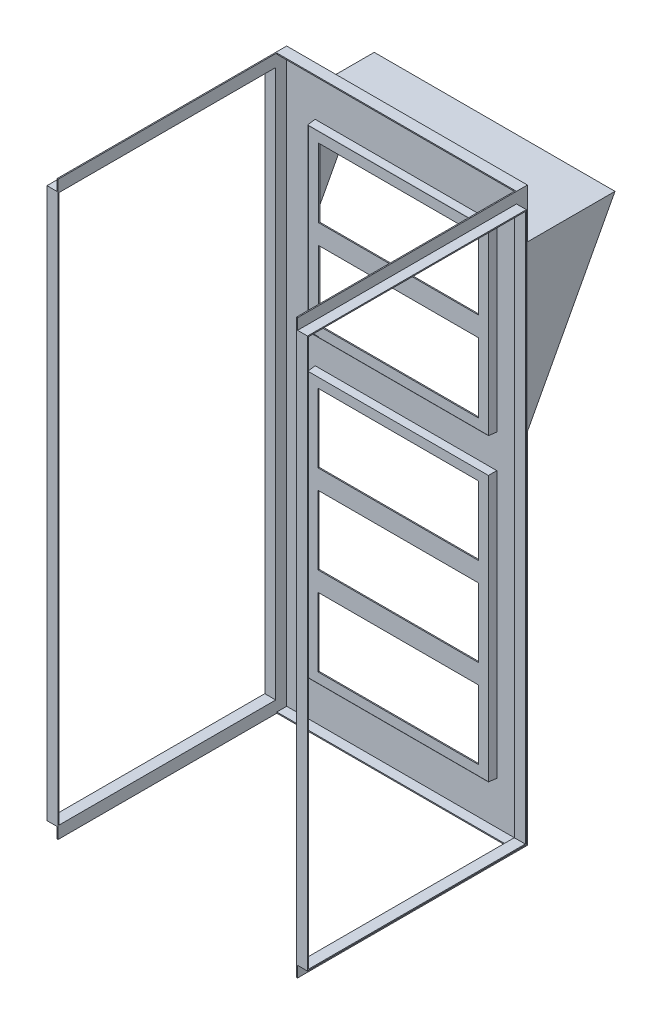
SolidWorks part; units mm, degrees
ref_plane "정면" through (0, 0, 0) normal (0, 0, 1) x (1, 0, 0)
ref_plane "윗면" through (0, 0, 0) normal (0, 1, 0) x (1, 0, 0)
ref_plane "우측면" through (0, 0, 0) normal (1, 0, 0) x (0, 0, -1)
sketch "스케치1" plane through (0, 0, 0) normal (0, 0, 1) x (1, 0, 0)
  line L1 (0, 0) -> (44, 0)
  line L2 (0, 0) -> (0, 104.5)
  line L3 (0, 104.5) -> (44, 104.5)
  line L4 (44, 0) -> (44, 104.5)
  dimension "D1" = 104.5
  dimension "D2" = 44
extrude "보스-돌출1" add sketch "스케치1" along normal blind 2
shell "쉘1" thickness 0.2
sketch "스케치2" plane through (0, 0, 0.2) normal (0, 0, 1) x (1, 0, 0)
  line L0 (44, 104.5) -> (0, 104.5) construction
  line L1 (5.6, 95.5) -> (38.4, 95.5)
  line L2 (5.6, 95.5) -> (5.6, 63)
  line L3 (5.6, 63) -> (38.4, 63)
  line L4 (38.4, 95.5) -> (38.4, 63)
  line L5 (5.6, 56.5) -> (38.4, 56.5)
  line L6 (5.6, 56.5) -> (5.6, 8.2)
  line L7 (5.6, 8.2) -> (38.4, 8.2)
  line L8 (38.4, 56.5) -> (38.4, 8.2)
  line L9 (0.2, 0.2) -> (43.8, 0.2) construction
  line L12 (0, 104.5) -> (0, 0) construction
  point P14 (22, 95.5)
  point P15 (22, 56.5)
  dimension "D1" = 9
  dimension "D2" = 32.5
  dimension "D3" = 6.5
  dimension "D4" = 8
  dimension "D5" = 32.8
  dimension "D6" = 32.8
  dimension "D7" = 22
  dimension "D8" = 22
extrude "컷-돌출1" cut sketch "스케치2" against normal blind 2
sketch "스케치3" plane through (0, 0, 0.2) normal (0, 0, 1) x (1, 0, 0)
  line L0 (5.6, 8.2) -> (38.4, 8.2) construction
  line L1 (5.6, 56.5) -> (5.6, 8.2) construction
  line L2 (38.4, 56.5) -> (5.6, 56.5) construction
  line L3 (38.4, 8.2) -> (38.4, 56.5) construction
  line L4 (5.6, 63) -> (38.4, 63)
  line L5 (5.6, 95.5) -> (5.6, 63)
  line L6 (38.4, 95.5) -> (5.6, 95.5)
  line L7 (38.4, 63) -> (38.4, 95.5)
  line L8 (5.6, 63) -> (38.4, 63)
  line L9 (5.6, 95.5) -> (5.6, 63)
  line L10 (38.4, 95.5) -> (5.6, 95.5)
  line L11 (38.4, 63) -> (38.4, 95.5)
  line L12 (5.6, 8.2) -> (38.4, 8.2)
  line L13 (5.6, 56.5) -> (5.6, 8.2)
  line L14 (38.4, 56.5) -> (5.6, 56.5)
  line L15 (38.4, 8.2) -> (38.4, 56.5)
  line L16 (5.4, 62.8) -> (38.6, 62.8)
  line L17 (38.6, 62.8) -> (38.6, 95.7)
  line L18 (38.6, 95.7) -> (5.4, 95.7)
  line L19 (5.4, 95.7) -> (5.4, 62.8)
  line L20 (5.4, 8) -> (38.6, 8)
  line L21 (38.6, 8) -> (38.6, 56.7)
  line L22 (38.6, 56.7) -> (5.4, 56.7)
  line L23 (5.4, 56.7) -> (5.4, 8)
  dimension "D1" = 0
  dimension "D2" = 0.2
extrude "보스-돌출2" add sketch "스케치3" along normal blind 1.8 draft 4
ref_plane "평면1" through (38.5, 95.6, 1.6301) normal (0, 1, 0) x (1, 0, 0)
ref_plane "평면2" through (0, 0, 1.4) normal (0, 0, 1) x (1, 0, 0)
sketch "스케치6" plane through (0, 0, 1.4) normal (0, 0, 1) x (1, 0, 0)
  line L0 (5.6, 63) -> (38.4, 63) construction
  line L1 (5.6, 95.5) -> (7.45, 95.5)
  line L2 (5.6, 95.5) -> (5.6, 63)
  line L3 (5.6, 63) -> (7.45, 63)
  line L4 (7.45, 95.5) -> (7.45, 63)
  line L6 (7.45, 64.75) -> (38.5, 64.75)
  line L7 (7.45, 64.75) -> (7.45, 62.9)
  line L8 (7.45, 62.9) -> (38.5, 62.9)
  line L9 (38.5, 64.75) -> (38.5, 62.9)
  line L11 (36.65, 64.75) -> (38.5, 64.75)
  line L12 (36.65, 64.75) -> (36.65, 95.6)
  line L13 (36.65, 95.6) -> (38.5, 95.6)
  line L14 (38.5, 64.75) -> (38.5, 95.6)
  line L15 (47.4925, 95.6) -> (29.5075, 95.6) construction
  line L16 (36.65, 93.65) -> (7.45, 93.65)
  line L17 (36.65, 93.65) -> (36.65, 95.5)
  line L18 (36.65, 95.5) -> (7.45, 95.5)
  line L19 (7.45, 93.65) -> (7.45, 95.5)
  line L20 (36.65, 77.45) -> (7.45, 77.45)
  line L21 (36.65, 77.45) -> (36.65, 81.05)
  line L22 (36.65, 81.05) -> (7.45, 81.05)
  line L23 (7.45, 77.45) -> (7.45, 81.05)
  line L24 (38.5, 62.9) -> (38.5, 95.6) construction
  dimension "D1" = 1.85
  dimension "D2" = 1.85
  dimension "D3" = 1.85
  dimension "D4" = 1.85
  dimension "D5" = 3.6
  dimension "D6" = 12.6
extrude "보스-돌출3" add sketch "스케치6" along normal blind 0.2 separate body contours L4 L1 L2 L3 | L9 L6 L4 L8 | L6 L14 L13 L12 | L12 L22 L4 L20 | L12 L18 L4 L16
sketch "스케치7" plane through (0, 0, 1.4) normal (0, 0, 1) x (1, 0, 0)
  line L1 (5.5, 56.6) -> (38.5, 56.6)
  line L2 (5.5, 56.6) -> (5.5, 8.1)
  line L3 (5.5, 8.1) -> (38.5, 8.1)
  line L4 (38.5, 56.6) -> (38.5, 8.1)
  line L5 (7.35, 22.5) -> (36.65, 22.5)
  line L6 (7.35, 22.5) -> (7.35, 9.9)
  line L7 (7.35, 9.9) -> (36.65, 9.9)
  line L8 (36.65, 22.5) -> (36.65, 9.9)
  line L9 (7.35, 38.65) -> (36.65, 38.65)
  line L10 (7.35, 38.65) -> (7.35, 26.05)
  line L11 (7.35, 26.05) -> (36.65, 26.05)
  line L12 (36.65, 38.65) -> (36.65, 26.05)
  line L13 (7.35, 54.8) -> (36.65, 54.8)
  line L14 (7.35, 54.8) -> (7.35, 42.2)
  line L15 (7.35, 42.2) -> (36.65, 42.2)
  line L16 (36.65, 54.8) -> (36.65, 42.2)
  dimension "D1" = 1.8
  dimension "D2" = 3.55
  dimension "D3" = 3.55
  dimension "D4" = 12.6
  dimension "D5" = 1.85
  dimension "D6" = 1.85
  dimension "D7" = 1.85
  dimension "D8" = 1.85
extrude "보스-돌출4" add sketch "스케치7" along normal blind 0.2
sketch "스케치11" plane through (0, 0, 0) normal (-1, 0, 0) x (0, 0, 1)
  line L0 (0, 95.5) -> (-16, 95.5)
  line L1 (0, 104.5) -> (0, 0) construction
  line L2 (-16, 95.5) -> (0, 65.5)
  line L3 (2, 104.5) -> (0, 104.5) construction
  line L4 (0, 95.5) -> (0, 65.5)
  dimension "D1" = 9
  dimension "D2" = 16
  dimension "D3" = 30
extrude "보스-돌출6" add sketch "스케치11" against normal blind 44 separate body
sketch "스케치12" plane through (0, 0, 0) normal (0, 0, -1) x (-1, 0, 0)
  line L36 (-0.2, 95.3) -> (-43.8, 95.3)
  line L37 (-43.8, 95.3) -> (-43.8, 65.5)
  line L38 (-43.8, 65.5) -> (-0.2, 65.5)
  line L39 (-0.2, 65.5) -> (-0.2, 95.3)
  line L48 (-5.6, 95.5) -> (-38.4, 95.5) construction
  line L49 (0, 95.5) -> (0, 65.5) construction
  line L51 (-44, 95.5) -> (-44, 65.5) construction
  line L52 (-44, 65.5) -> (0, 65.5) construction
  dimension "D1" = 0.2
  dimension "D2" = 0.2
  dimension "D4" = 0.2
extrude "컷-돌출5" cut sketch "스케치12" along normal blind 16
ref_plane "평면3" through (44, 0, 0) normal (1, 0, 0) x (0, 0, -1)
sketch "스케치13" plane through (43.8, 0, 0) normal (-1, 0, 0) x (0, 0, 1)
  line L0 (2, 104.5) -> (2, 0) construction
  line L1 (2, 102.5) -> (42, 102.5)
  line L2 (2, 102.5) -> (2, 2)
  line L3 (2, 2) -> (42, 2)
  line L4 (42, 102.5) -> (42, 2)
  line L5 (2, 104.5) -> (0, 104.5) construction
  line L6 (41.8, 2.2) -> (2.2, 2.2)
  line L7 (41.8, 2.2) -> (41.8, 102.3)
  line L8 (41.8, 102.3) -> (2.2, 102.3)
  line L9 (2.2, 2.2) -> (2.2, 102.3)
  line L10 (2, 0) -> (0, 0) construction
  line L11 (0, 65.5) -> (0, 95.5) construction
  dimension "D1" = 2
  dimension "D2" = 2
  dimension "D3" = 0.2
  dimension "D4" = 0.2
  dimension "D5" = 0.2
  dimension "D6" = 0.2
  dimension "D7" = 42
extrude "보스-돌출7" add sketch "스케치13" against normal blind 2
sketch "스케치15" plane through (0.2, 0, 0) normal (1, 0, 0) x (0, 0, -1)
  line L0 (-2, 0) -> (-2, 2) construction
  line L1 (-42, 102.5) -> (-2, 102.5)
  line L2 (-42, 102.5) -> (-42, 2)
  line L3 (-42, 2) -> (-2, 2)
  line L4 (-2, 102.5) -> (-2, 2)
  line L6 (-2.2, 2.2) -> (-41.8, 2.2)
  line L7 (-2.2, 2.2) -> (-2.2, 102.3)
  line L8 (-2.2, 102.3) -> (-41.8, 102.3)
  line L9 (-41.8, 2.2) -> (-41.8, 102.3)
extrude "보스-돌출8" add sketch "스케치15" against normal blind 2
sketch "스케치16" plane through (0, 0, 2) normal (0, 0, 1) x (1, 0, 0)
  line L0 (44, -0.99) -> (44, 0.99) construction
  line L1 (44, 102.5) -> (43.8, 102.5)
  line L2 (44, 102.5) -> (44, 104.5)
  line L3 (44, 104.5) -> (43.8, 104.5)
  line L4 (43.8, 102.5) -> (43.8, 104.5)
  line L5 (45.8, 102.5) -> (43.8, 102.5) construction
  line L6 (43.8, 0.2) -> (43.8, 2) construction
  line L7 (43.8, 0) -> (44, 0)
  line L8 (43.8, 0) -> (43.8, 2)
  line L9 (43.8, 2) -> (44, 2)
  line L10 (44, 0) -> (44, 2)
  line L12 (45.8, 2) -> (44, 2) construction
  line L13 (44, 2) -> (43.8, 2) construction
  line L14 (0, 104.5) -> (0, 102.5) construction
  line L15 (0.2, 0) -> (0, 0)
  line L16 (0.2, 0) -> (0.2, 2)
  line L17 (0.2, 2) -> (0, 2)
  line L18 (0, 0) -> (0, 2)
  line L19 (0.2, 104.5) -> (0, 104.5)
  line L20 (0.2, 104.5) -> (0.2, 102.5)
  line L21 (0.2, 102.5) -> (0, 102.5)
  line L22 (0, 104.5) -> (0, 102.5)
  line L23 (-1.8, 102.5) -> (0.2, 102.5) construction
  line L24 (44, 0) -> (44, 2) construction
  line L25 (44, 104.5) -> (0, 104.5) construction
  line L26 (0, 0) -> (44, 0) construction
  point P15 (43.8, 0)
  point P34 (0, 103.6228)
  point P35 (0, 103.6233)
  point P38 (43.985, 2)
  point P39 (44.0045, 2)
  point P40 (44, 0.2)
  point P43 (0.1808, 104.5)
  point P47 (43.817, 104.5)
  point P49 (0.1725, 0)
extrude "보스-돌출9" add sketch "스케치16" along normal blind 40
